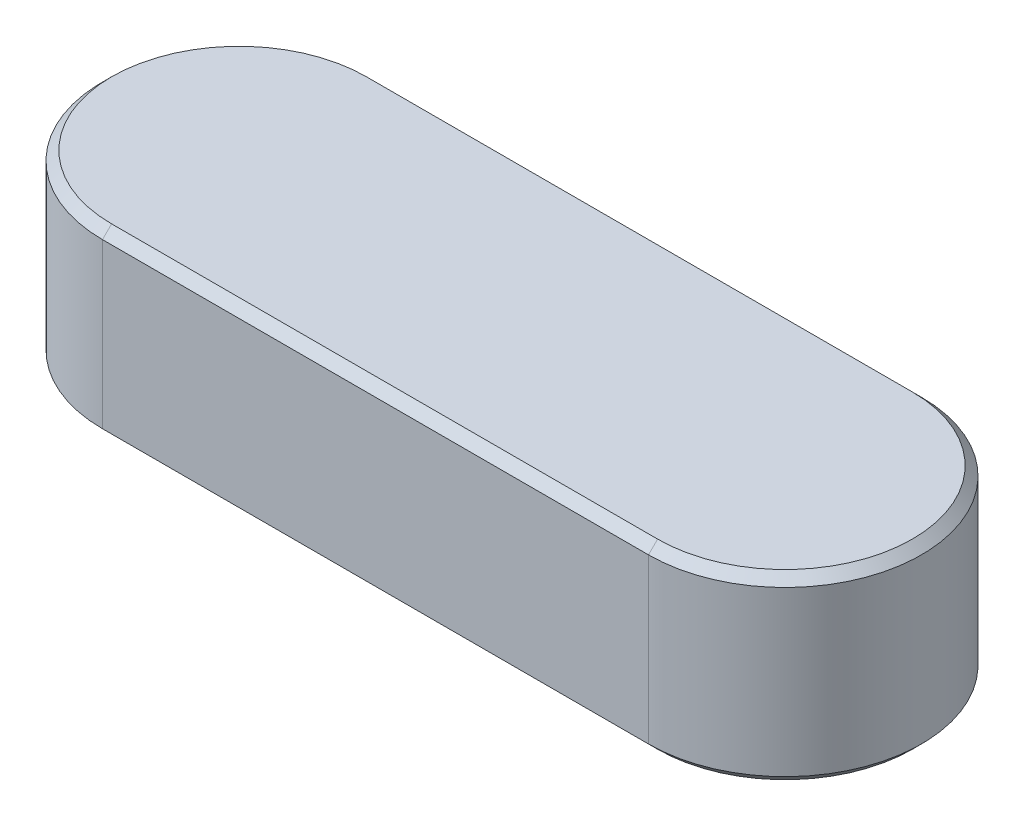
SolidWorks part; units mm, degrees
ref_plane "前视基准面" through (0, 0, 0) normal (0, 0, 1) x (1, 0, 0)
ref_plane "上视基准面" through (0, 0, 0) normal (0, 1, 0) x (1, 0, 0)
ref_plane "右视基准面" through (0, 0, 0) normal (1, 0, 0) x (0, 0, -1)
sketch "草图1" plane through (0, 0, 0) normal (0, 1, 0) x (1, 0, 0)
  line L1 (-12, 6) -> (12, 6)
  line L3 (-12, -6) -> (12, -6)
  arc A0 (12, -6) -> (12, 6) centre (12, 0) ccw
  arc A1 (-12, 6) -> (-12, -6) centre (-12, 0) ccw
extrude "凸台-拉伸1" add sketch "草图1" along normal blind 8
chamfer "倒角1" distance 0.4 distance2 0.4 4 edges at (0, 8, -6) (18, 8, 0) (-18, 8, 0) (0, 8, 6)
chamfer "倒角2" distance 0.4 angle 45 4 edges at (-18, 0, 0) (0, 0, 6) (0, 0, -6) (18, 0, 0)
